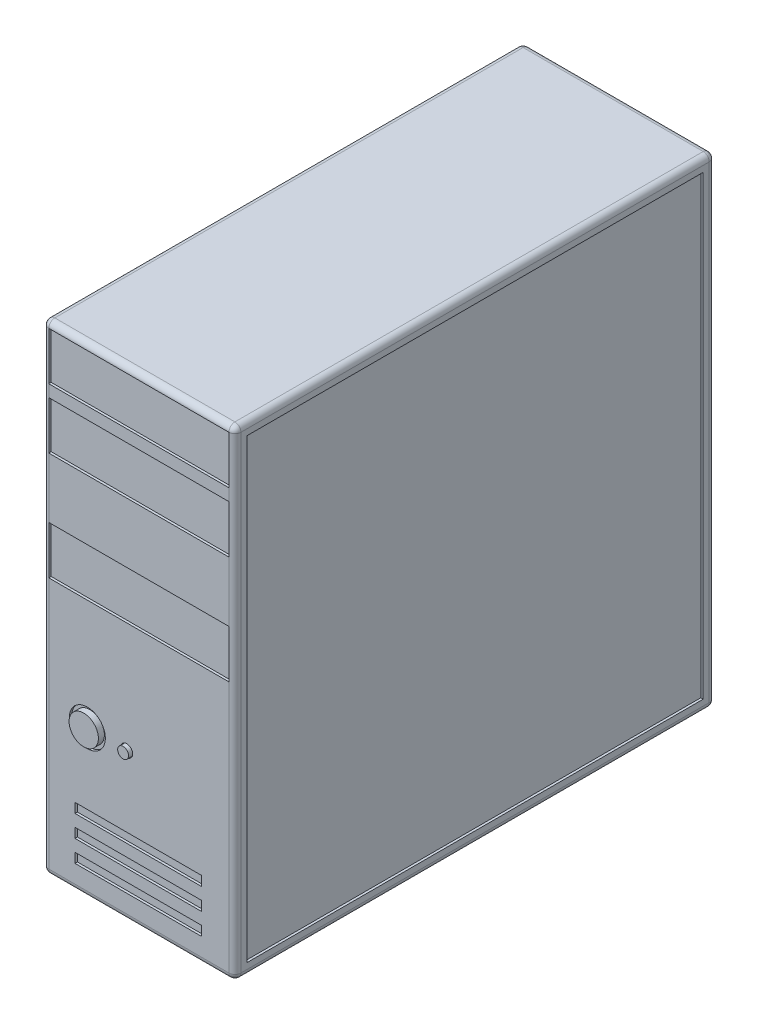
SolidWorks part; units mm, degrees
ref_plane "Alzado" through (0, 0, 0) normal (0, 0, 1) x (1, 0, 0)
ref_plane "Planta" through (0, 0, 0) normal (0, 1, 0) x (1, 0, 0)
ref_plane "Vista lateral" through (0, 0, 0) normal (1, 0, 0) x (0, 0, -1)
sketch "Croquis1" plane through (0, 0, 0) normal (0, 0, 1) x (1, 0, 0)
  line L0 (80, 200) -> (-80, -200) construction
  line L1 (-80, 200) -> (80, 200)
  line L2 (-80, 200) -> (-80, -200)
  line L3 (-80, -200) -> (80, -200)
  line L4 (80, 200) -> (80, -200)
  dimension "D1" = 160
  dimension "D2" = 400
extrude "Saliente-Extruir1" add sketch "Croquis1" against normal blind 400
fillet "Redondeo1" radius 5 12 edges at (-80, 200, -200) (80, 200, -200) (80, -200, -200) (-80, -200, -200) (0, 200, -400) (80, 0, -400) (0, -200, -400) (-80, 0, -400) (0, 200, 0) (80, 0, 0) (0, -200, 0) (-80, 0, 0)
sketch "Croquis2" plane through (0, 0, 0) normal (0, 0, 1) x (1, 0, 0)
  line L0 (75, -195) -> (75, 195) construction
  line L1 (-75, 195) -> (75, 195)
  line L2 (-75, 195) -> (-75, 155)
  line L3 (-75, 155) -> (75, 155)
  line L4 (75, 195) -> (75, 155)
  line L5 (-75, 195) -> (-75, -195) construction
  line L6 (-75, 145) -> (75, 145)
  line L7 (-75, 145) -> (-75, 105)
  line L8 (-75, 105) -> (75, 105)
  line L9 (75, 145) -> (75, 105)
  line L10 (-75, -195) -> (75, -195) construction
  line L11 (-75, 55) -> (75, 55)
  line L12 (-75, 55) -> (-75, 15)
  line L13 (-75, 15) -> (75, 15)
  line L14 (75, 55) -> (75, 15)
  line L15 (-53.2227, -172) -> (52.2922, -172)
  line L16 (-53.2227, -172) -> (-53.2227, -180)
  line L17 (-53.2227, -180) -> (52.2922, -180)
  line L18 (52.2922, -172) -> (52.2922, -180)
  line L19 (-53.2227, -154) -> (52.2922, -154)
  line L20 (-53.2227, -154) -> (-53.2227, -162)
  line L21 (-53.2227, -162) -> (52.2922, -162)
  line L22 (52.2922, -154) -> (52.2922, -162)
  line L23 (-53.2227, -136) -> (52.2922, -136)
  line L24 (-53.2227, -136) -> (-53.2227, -144)
  line L25 (-53.2227, -144) -> (52.2922, -144)
  line L26 (52.2922, -136) -> (52.2922, -144)
  line L27 (-75, -77.1379) -> (75, -77.1379) construction
  circle A0 centre (-42.9064, -77.1379) radius 15
  circle A1 centre (-10.118, -77.1379) radius 5
  dimension "D12" = 30
  dimension "D13" = 10
  dimension "D1" = 10
  dimension "D2" = 10
  dimension "D3" = 15
  dimension "D4" = 8
  dimension "D5" = 8
  dimension "D6" = 8
  dimension "D7" = 40
  dimension "D8" = 10
  dimension "D9" = 40
  dimension "D10" = 50
  dimension "D11" = 40
extrude "Cortar-Extruir1" cut sketch "Croquis2" against normal blind 2
sketch "Croquis3" plane through (0, 0, -2) normal (0, 0, 1) x (1, 0, 0)
  circle A0 centre (-42.9064, -77.1379) radius 12.2037
  circle A1 centre (-10.118, -77.1379) radius 4.5213
extrude "Saliente-Extruir2" add sketch "Croquis3" along normal blind 5
sketch "Croquis4" plane through (-80, 0, 0) normal (-1, 0, 0) x (0, 0, 1)
  line L0 (-5, 195) -> (-395, 195) construction
  line L1 (-390, 190) -> (-10, 190)
  line L2 (-390, 190) -> (-390, -190)
  line L3 (-390, -190) -> (-10, -190)
  line L4 (-10, 190) -> (-10, -190)
  line L5 (-395, 195) -> (-395, -195) construction
  line L6 (-5, -195) -> (-5, 195) construction
  line L7 (-395, -195) -> (-5, -195) construction
  dimension "D1" = 5
  dimension "D2" = 5
  dimension "D3" = 5
  dimension "D4" = 5
extrude "Cortar-Extruir2" cut sketch "Croquis4" against normal blind 2
sketch "Croquis5" plane through (80, 0, 0) normal (1, 0, 0) x (0, 0, -1)
  line L0 (395, 195) -> (5, 195) construction
  line L1 (10, 190) -> (390, 190)
  line L2 (10, 190) -> (10, -190)
  line L3 (10, -190) -> (390, -190)
  line L4 (390, 190) -> (390, -190)
  line L5 (395, -195) -> (395, 195) construction
  line L6 (5, -195) -> (395, -195) construction
  line L7 (5, 195) -> (5, -195) construction
  dimension "D1" = 5
  dimension "D2" = 5
  dimension "D3" = 5
  dimension "D4" = 5
extrude "Cortar-Extruir3" cut sketch "Croquis5" against normal blind 2
